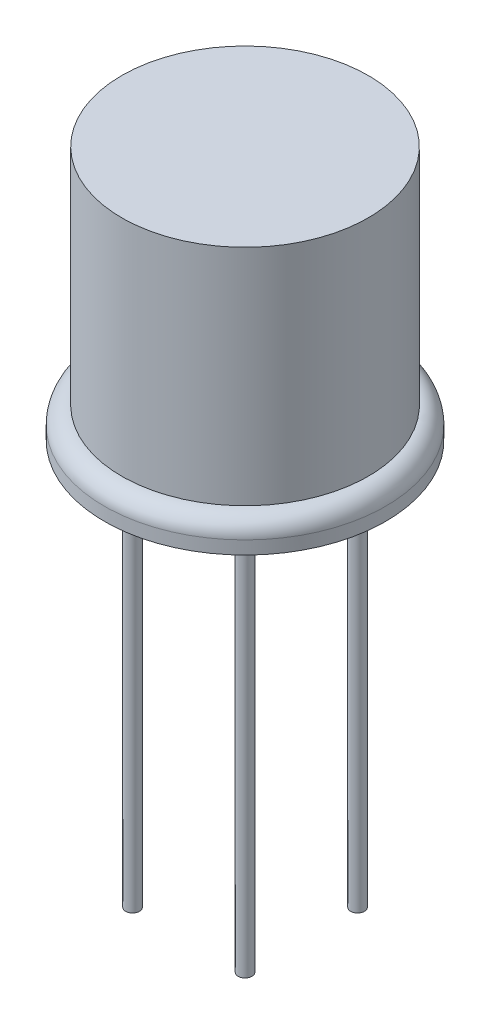
SolidWorks part; units mm, degrees
ref_plane "Front Plane" through (0, 0, 0) normal (0, 0, 1) x (1, 0, 0)
ref_plane "Top Plane" through (0, 0, 0) normal (0, 1, 0) x (1, 0, 0)
ref_plane "Right Plane" through (0, 0, 0) normal (1, 0, 0) x (0, 0, -1)
sketch "Sketch2" plane through (0, 0, 0) normal (0, 1, 0) x (1, 0, 0)
  line L0 (-0.4445, 4.6141) -> (-0.4445, 5.2491)
  line L1 (-0.4445, 5.2491) -> (0.4445, 5.2491)
  line L2 (0.4445, 5.2491) -> (0.4445, 4.6141)
  arc A0 (-0.4445, 4.6141) -> (0.4445, 4.6141) centre (0, 0) ccw
  point P5 (0, 5.2491)
  dimension "D1" = 9.271
  dimension "D2" = 0.889
  dimension "D3" = 0.635
extrude "Boss-Extrude1" add sketch "Sketch2" along normal blind 0.4318
sketch "Sketch4" plane through (0, 0, 0) normal (0, 0, 1) x (1, 0, 0)
  line L0 (4.6355, 0.4318) -> (-4.6355, 0.4318) construction
  line L1 (4.064, 1.0033) -> (4.064, 8.382)
  line L2 (4.064, 8.382) -> (0, 8.382)
  line L3 (0, 8.382) -> (0, 0.4318)
  line L4 (0, 0.4318) -> (4.6355, 0.4318)
  line L5 (-4.6355, 0) -> (4.6355, 0) construction
  line L6 (-4.6355, 0) -> (4.6355, 0) construction
  line L7 (4.6355, 0) -> (4.6355, 0.4318) construction
  line L8 (4.064, 0.4318) -> (4.064, 1.0033) construction
  arc A0 (4.6355, 0.4318) -> (4.064, 1.0033) centre (4.064, 0.4318) ccw
  dimension "D1" = 8.382
  dimension "D2" = 4.064
revolve "Revolve1" add sketch "Sketch4" angle 360 about L3
sketch "Sketch5" plane through (0, 0, 0) normal (0, -1, 0) x (1, 0, 0)
  line L1 (1.8542, -1.8542) -> (-1.8542, -1.8542) construction
  line L2 (1.8542, -1.8542) -> (1.8542, 1.8542) construction
  line L3 (1.8542, 1.8542) -> (-1.8542, 1.8542) construction
  line L4 (-1.8542, -1.8542) -> (-1.8542, 1.8542) construction
  line L5 (1.8542, -1.8542) -> (-1.8542, 1.8542) construction
  line L6 (1.8542, 1.8542) -> (-1.8542, -1.8542) construction
  circle A0 centre (-1.8542, -1.8542) radius 0.2286
  circle A1 centre (1.8542, -1.8542) radius 0.2286
  circle A2 centre (1.8542, 1.8542) radius 0.2286
  circle A3 centre (-1.8542, 1.8542) radius 0.2286
  point P0 (0, 0)
  dimension "D1" = 0.4572
  dimension "D2" = 3.7084
extrude "Boss-Extrude2" add sketch "Sketch5" along normal blind 13.335
sketch "Sketch6" plane through (0, 0, 0) normal (0, 0, 1) x (1, 0, 0)
  line L4 (0, 8.382) -> (0, 262.382)
  line L5 (4.064, 8.382) -> (-4.064, 8.382) construction
  line L6 (0, 262.382) -> (26.2861, 262.382)
  line L7 (26.2861, 262.382) -> (4.064, 8.382)
  line L8 (4.064, 8.382) -> (0, 8.382)
  dimension "D1" = 5
  dimension "D2" = 254
revolve "Revolve2" [suppressed] add sketch "Sketch6" angle 360 about L4
